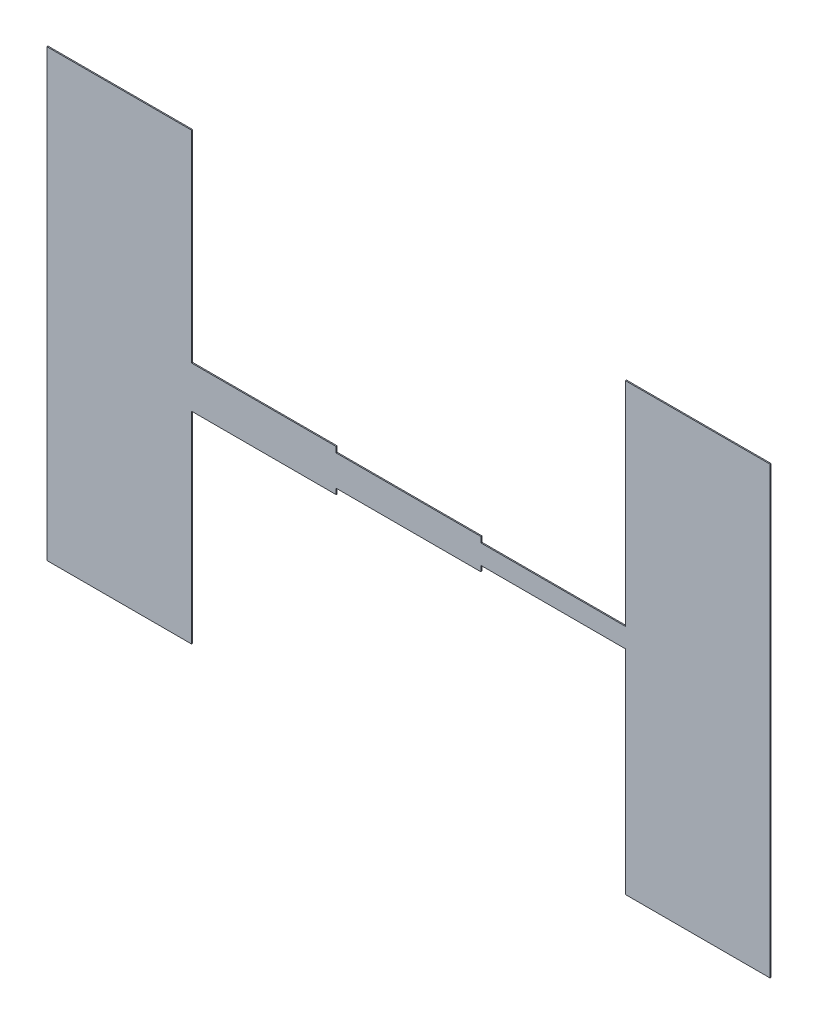
SolidWorks part; units mm, degrees
ref_plane "Front Plane" through (0, 0, 0) normal (0, 0, 1) x (1, 0, 0)
ref_plane "Top Plane" through (0, 0, 0) normal (0, 1, 0) x (1, 0, 0)
ref_plane "Right Plane" through (0, 0, 0) normal (1, 0, 0) x (0, 0, -1)
sketch "Sketch1" plane through (0, 0, 0) normal (0, 0, 1) x (1, 0, 0)
  line L0 (0, 0) -> (650, 0)
  line L1 (-650, -2000) -> (650, -2000)
  line L2 (-650, -2000) -> (-650, 2000)
  line L3 (-650, 2000) -> (650, 2000)
  line L4 (650, -2000) -> (650, -187.5)
  line L5 (-650, -2000) -> (650, 2000) construction
  line L6 (-650, 2000) -> (650, -2000) construction
  line L7 (650, 0) -> (7529.1767, 0) construction
  line L8 (650, 187.5) -> (650, 2000)
  line L9 (1950, -187.5) -> (650, -187.5)
  line L10 (1950, -187.5) -> (1950, -137.5)
  line L11 (1950, 187.5) -> (650, 187.5)
  line L13 (1950, -187.5) -> (650, 187.5) construction
  line L14 (1950, 187.5) -> (650, -187.5) construction
  line L15 (3250, -137.5) -> (1950, -137.5)
  line L16 (3250, -137.5) -> (3250, -87.5)
  line L17 (3250, 137.5) -> (1950, 137.5)
  line L19 (3250, -137.5) -> (1950, 137.5) construction
  line L20 (3250, 137.5) -> (1950, -137.5) construction
  line L21 (4550, -87.5) -> (3250, -87.5)
  line L23 (4550, 87.5) -> (3250, 87.5)
  line L25 (4550, -87.5) -> (3250, 87.5) construction
  line L26 (4550, 87.5) -> (3250, -87.5) construction
  line L27 (1950, 137.5) -> (1950, 187.5)
  line L28 (3250, 87.5) -> (3250, 137.5)
  line L29 (4550, 87.5) -> (4550, 2000)
  line L30 (5850, -2000) -> (4550, -2000)
  line L31 (5850, -2000) -> (5850, 2000)
  line L32 (5850, 2000) -> (4550, 2000)
  line L33 (4550, -2000) -> (4550, -87.5)
  line L34 (5850, -2000) -> (4550, 2000) construction
  line L35 (5850, 2000) -> (4550, -2000) construction
  point P0 (0, 0)
  point P9 (1300, 0)
  point P14 (2600, 0)
  point P19 (3900, 0)
  point P24 (5200, 0)
  dimension "D1" = 1300
  dimension "D2" = 4000
  dimension "D3" = 375
  dimension "D4" = 1300
  dimension "D5" = 1300
  dimension "D6" = 1300
  dimension "D7" = 175
  dimension "D8" = 275
  dimension "D9" = 1300
  dimension "D10" = 4000
extrude "Boss-Extrude1" add sketch "Sketch1" along normal blind 10
